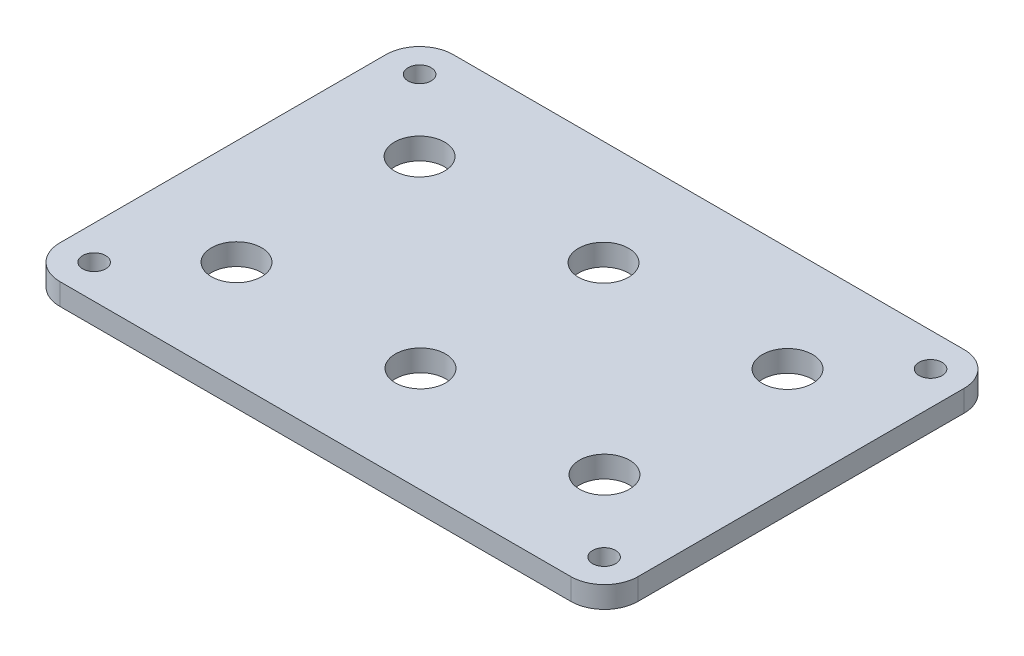
SolidWorks part; units mm, degrees
ref_plane "Front Plane" through (0, 0, 0) normal (0, 0, 1) x (1, 0, 0)
ref_plane "Top Plane" through (0, 0, 0) normal (0, 1, 0) x (1, 0, 0)
ref_plane "Right Plane" through (0, 0, 0) normal (1, 0, 0) x (0, 0, -1)
sketch "Sketch1" plane through (0, 0, 0) normal (0, 1, 0) x (1, 0, 0)
  line L0 (107.4879, 137.3364) -> (32.1345, 137.3364)
  line L1 (27.178, 142.2929) -> (27.178, 190.3801)
  line L2 (32.1345, 195.3366) -> (107.4879, 195.3366)
  line L3 (112.4444, 190.3801) -> (112.4444, 142.2929)
  circle A0 centre (42.6791, 179.8355) radius 3.7006
  circle A1 centre (69.8112, 179.8355) radius 3.7006
  circle A2 centre (96.9469, 179.8355) radius 3.7006
  circle A3 centre (42.6791, 152.8374) radius 3.7006
  circle A4 centre (69.8112, 152.8374) radius 3.7006
  circle A5 centre (96.9469, 152.8374) radius 3.7006
  circle A6 centre (32.1804, 190.3377) radius 1.7004
  circle A7 centre (32.1804, 142.3388) radius 1.7004
  circle A8 centre (107.4455, 142.2859) radius 1.7004
  circle A9 centre (107.4949, 190.3871) radius 1.7004
  spline S0 degree 3 poles (32.1345, 137.3364) (29.397, 137.3364) (27.178, 139.5554) (27.178, 142.2929) knots 1 1 1 1 2 2 2 2
  spline S1 degree 3 poles (27.178, 190.3801) (27.178, 193.1176) (29.397, 195.3366) (32.1345, 195.3366) knots 3 3 3 3 4 4 4 4
  spline S2 degree 3 poles (107.4879, 195.3366) (110.2254, 195.3366) (112.4444, 193.1176) (112.4444, 190.3801) knots 5 5 5 5 6 6 6 6
  spline S3 degree 3 poles (112.4444, 142.2929) (112.4444, 139.5554) (110.2254, 137.3364) (107.4879, 137.3364) knots 7 7 7 7 8 8 8 8
extrude "Boss-Extrude1" add sketch "Sketch1" along normal blind 3.175
